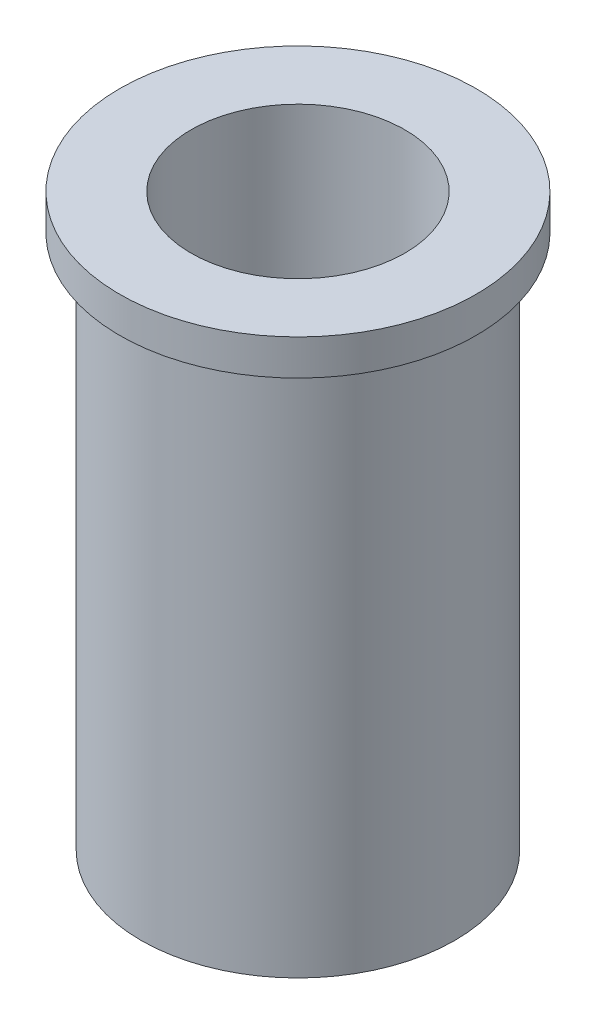
SolidWorks part; units mm, degrees
ref_plane "Front Plane" through (0, 0, 0) normal (0, 0, 1) x (1, 0, 0)
ref_plane "Top Plane" through (0, 0, 0) normal (0, 1, 0) x (1, 0, 0)
ref_plane "Right Plane" through (0, 0, 0) normal (1, 0, 0) x (0, 0, -1)
sketch "Sketch2" plane through (0, 0, 0) normal (0, 0, 1) x (1, 0, 0)
  line L0 (-5, 2.8721) -> (0, 2.8721)
  line L4 (0, -13.1279) -> (-4.4, -13.1279)
  line L5 (-4.4, -13.1279) -> (-4.4, 1.8721)
  line L6 (-4.4, 1.8721) -> (-5, 1.8721)
  line L7 (-5, 1.8721) -> (-5, 2.8721)
  line L8 (0, 2.8721) -> (0, -13.1279)
  dimension "D1" = 16
revolve "Revolve3" add sketch "Sketch2" angle 360 about L8
sketch "Sketch4" plane through (0, -13.1279, 0) normal (0, -1, 0) x (1, 0, 0)
  circle A0 centre (0, 0) radius 3
  dimension "D1" = 6
extrude "Boss-Extrude1" add sketch "Sketch4" against normal blind 16
sketch "Sketch5" plane through (0, -13.1279, 0) normal (0, -1, 0) x (1, 0, 0)
  circle A0 centre (0, 0) radius 3
  dimension "D1" = 6
extrude "Cut-Extrude1" cut sketch "Sketch5" against normal blind 16
